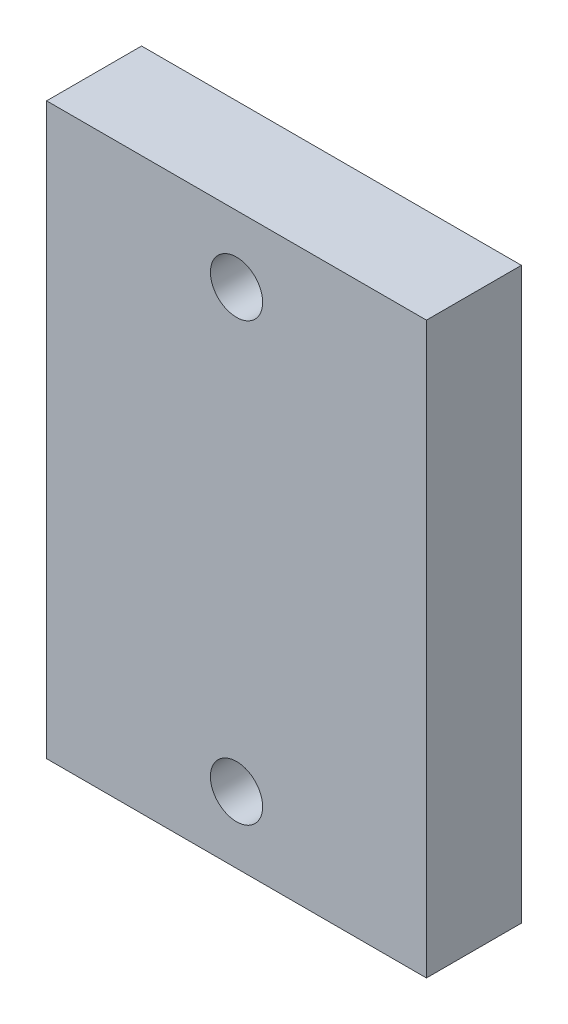
SolidWorks part; units mm, degrees
ref_plane "前视基准面" through (0, 0, 0) normal (0, 0, 1) x (1, 0, 0)
ref_plane "上视基准面" through (0, 0, 0) normal (0, 1, 0) x (1, 0, 0)
ref_plane "右视基准面" through (0, 0, 0) normal (1, 0, 0) x (0, 0, -1)
other "Configuration Table"
sketch "草图1" plane through (0, 0, 0) normal (0, 0, 1) x (1, 0, 0)
  line L1 (-20, -30) -> (20, -30)
  line L2 (-20, -30) -> (-20, 30)
  line L3 (-20, 30) -> (20, 30)
  line L4 (20, -30) -> (20, 30)
  line L5 (-20, -30) -> (20, 30) construction
  line L6 (-20, 30) -> (20, -30) construction
  point P0 (0, 0)
  dimension "D1" = 40
  dimension "D2" = 60
extrude "凸台-拉伸1" add sketch "草图1" along normal blind 10
sketch "草图2" plane through (0, 0, 10) normal (0, 0, 1) x (1, 0, 0)
  line L0 (0, -30) -> (0, 30) construction
  line L1 (-20, -30) -> (20, -30) construction
  line L2 (20, 30) -> (-20, 30) construction
  circle A0 centre (0, -23) radius 2.75
  circle A1 centre (0, 23) radius 2.75
  dimension "D2" = 46
  dimension "D3" = 5.5
  dimension "D4" = 5.5
  dimension "D1" = 7
extrude "切除-拉伸1" cut sketch "草图2" against normal blind 10
